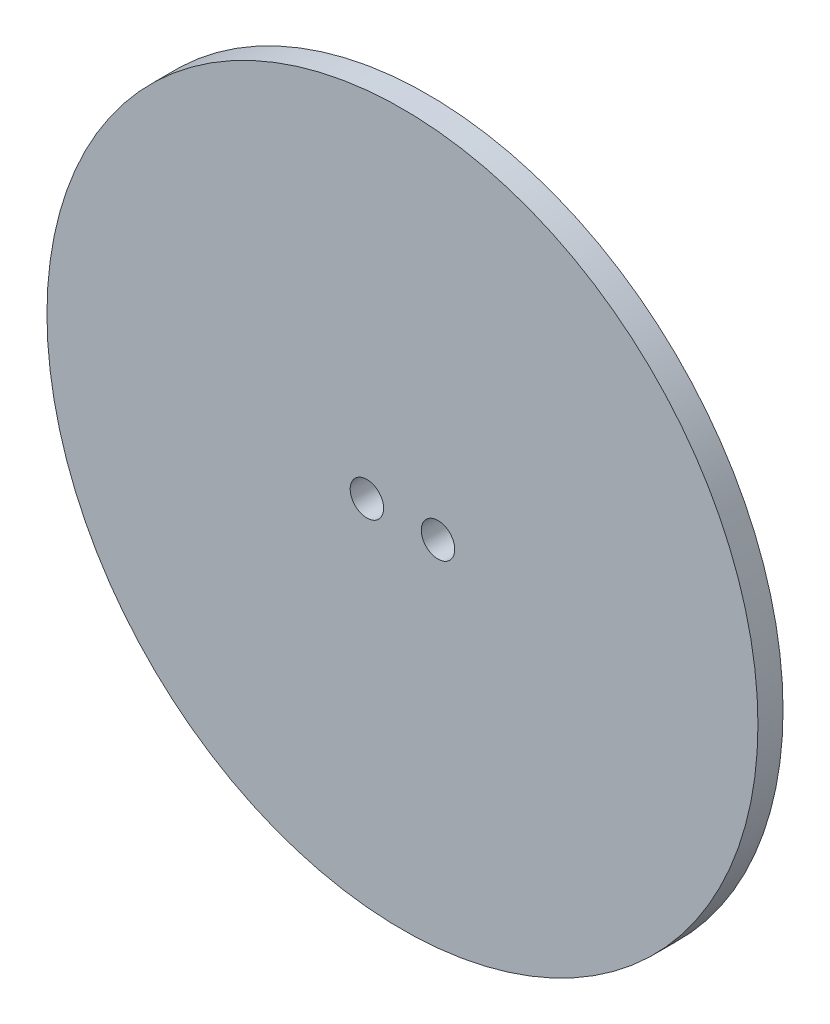
SolidWorks part; units mm, degrees
ref_plane "前视基准面" through (0, 0, 0) normal (0, 0, 1) x (1, 0, 0)
ref_plane "上视基准面" through (0, 0, 0) normal (0, 1, 0) x (1, 0, 0)
ref_plane "右视基准面" through (0, 0, 0) normal (1, 0, 0) x (0, 0, -1)
other "Configuration Table"
sketch "草图1" plane through (0, 0, 0) normal (0, 0, 1) x (1, 0, 0)
  circle A0 centre (0, 0) radius 42.5
  dimension "D1" = 85
extrude "凸台-拉伸1" add sketch "草图1" along normal blind 3
sketch "草图2" plane through (0, 0, 0) normal (0, 0, -1) x (-1, 0, 0)
  line L0 (0, 0) -> (42.5, 0) construction
  circle A0 centre (0, 0) radius 42.5 construction
  circle A1 centre (4.25, 0) radius 2
  circle A2 centre (-4.25, 0) radius 2
  dimension "D1" = 4
  dimension "D2" = 4
  dimension "D3" = 8.5
  dimension "D4" = 38.25
extrude "切除-拉伸1" cut sketch "草图2" against normal up to next
